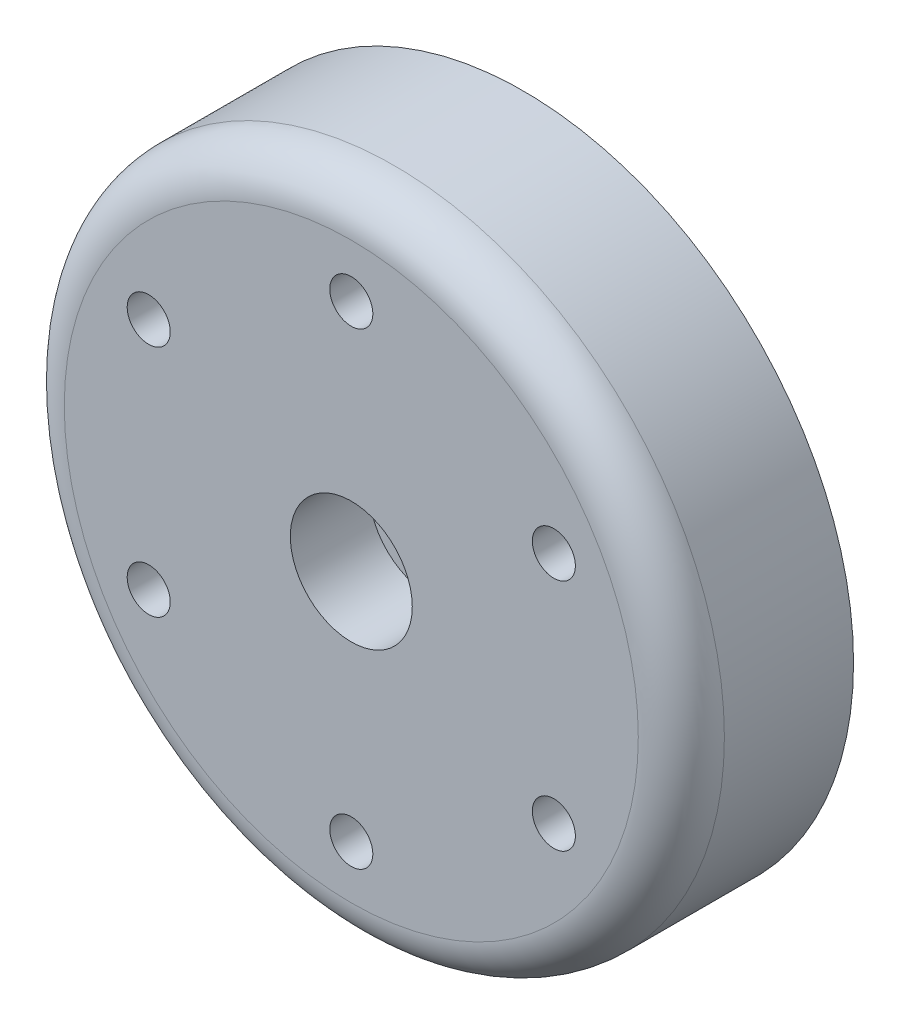
SolidWorks part; units mm, degrees
material "AISI 316 Annealed Stainless Steel Bar (SS)"
ref_plane "Front Plane" through (0, 0, 0) normal (0, 0, 1) x (1, 0, 0)
ref_plane "Top Plane" through (0, 0, 0) normal (0, 1, 0) x (1, 0, 0)
ref_plane "Right Plane" through (0, 0, 0) normal (1, 0, 0) x (0, 0, -1)
sketch "Sketch1" plane through (0, 0, 0) normal (0, 0, 1) x (1, 0, 0)
  circle A0 centre (0, 0) radius 23
  circle A2 centre (0, 16.3) radius 1.5
  circle A3 centre (14.1162, 8.15) radius 1.5
  circle A4 centre (14.1162, -8.15) radius 1.5
  circle A5 centre (0, -16.3) radius 1.5
  circle A6 centre (-14.1162, -8.15) radius 1.5
  circle A7 centre (-14.1162, 8.15) radius 1.5
  point P19 (0, 0)
  dimension "D1" = 46
  dimension "D3" = 3
  dimension "D4" = 16.3
  dimension "D5" = 6
extrude "Boss-Extrude1" add sketch "Sketch1" along normal blind 12
sketch "Sketch2" plane through (0, 0, 0) normal (0, 0, -1) x (-1, 0, 0)
  circle A0 centre (0, 0) radius 20
  circle A1 centre (0, 0) radius 12.7
  dimension "D1" = 40
  dimension "D2" = 25.4
extrude "Cut-Extrude1" cut sketch "Sketch2" against normal blind 6
fillet "Fillet1" radius 3 1 edges at (23, 0, 12)
hole_wizard "CBORE for M5 Hex Head Bolt1" positions "Sketch3" profile "Sketch4" counterbore size "M5" standard "ANSI Metric" end condition through all
sketch "Sketch3" plane through (0, 0, 12) normal (0, 0, 1) x (1, 0, 0)
  point P0 (0, 0)
sketch "Sketch4" plane through (0, 0, 12) normal (1, 0, 0) x (0, -1, 0)
  line L0 (0, 0) -> (0, 12)
  line L1 (0, 12) -> (2.5, 12)
  line L3 (2.5, 12) -> (2.5, 5.5)
  line L4 (2.5, 5.5) -> (4.25, 5.5)
  line L5 (4.25, 5.5) -> (4.25, 0)
  line L7 (4.25, 0) -> (0, 0)
  line L11 (0, -6.35) -> (0, 107.95) construction
  dimension "Thru Hole Dia." = 5
  dimension "Thru Hole Depth" = 12
  dimension "C'Bore Dia." = 8.5
  dimension "C'Bore Depth" = 5.5
sketch "Sketch5" plane through (0, 0, 0) normal (0, 0, -1) x (-1, 0, 0)
  circle A0 centre (0, 0) radius 8.5
  dimension "D1" = 17
extrude "Cut-Extrude2" cut sketch "Sketch5" against normal blind 2
